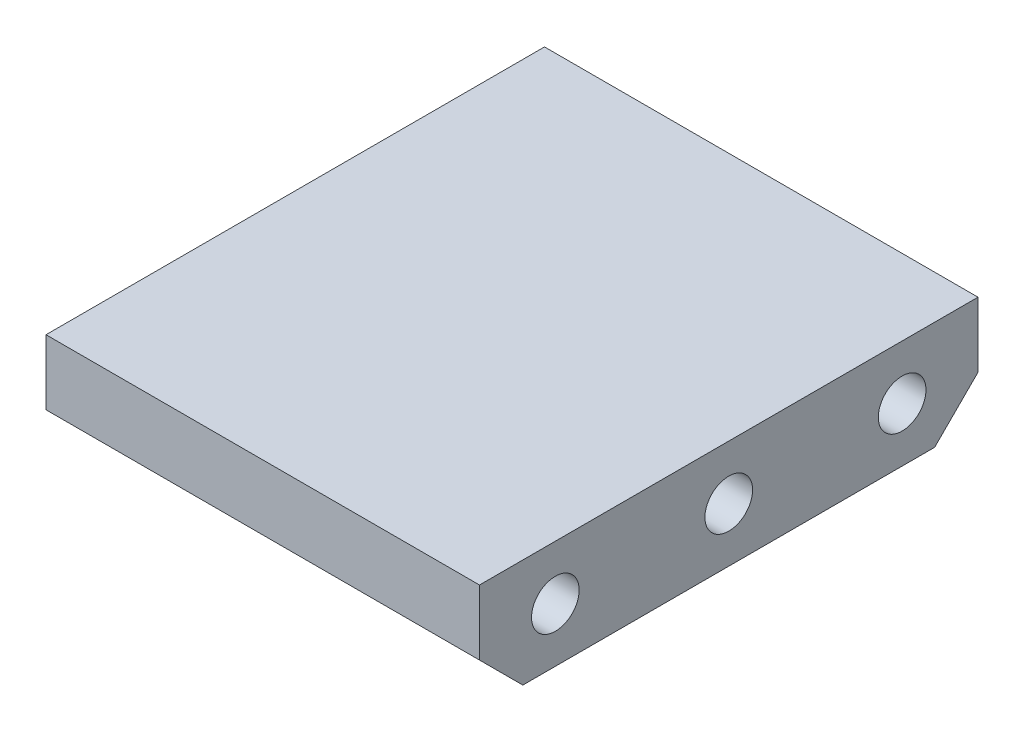
SolidWorks part; units mm, degrees
ref_plane "Ebene vorne" through (0, 0, 0) normal (0, 0, 1) x (1, 0, 0)
ref_plane "Ebene oben" through (0, 0, 0) normal (0, 1, 0) x (1, 0, 0)
ref_plane "Ebene rechts" through (0, 0, 0) normal (1, 0, 0) x (0, 0, -1)
sketch "Skizze1" plane through (0, 0, 0) normal (1, 0, 0) x (0, 0, -1)
  line L0 (-115, 0) -> (115, 0)
  line L1 (115, 0) -> (115, -30)
  line L2 (115, -30) -> (95, -50)
  line L3 (95, -50) -> (-95, -50)
  line L4 (0, 31.095) -> (0, -59.3631) construction
  line L5 (-115, -30) -> (-95, -50)
  line L6 (-115, 0) -> (-115, -30)
  circle A0 centre (0, -25) radius 11
  circle A1 centre (-80, -25) radius 11
  circle A2 centre (80, -25) radius 11
  point P9 (0, -50)
  point P11 (0, 0)
  dimension "D1" = 22
  dimension "D2" = 22
  dimension "D3" = 50
  dimension "D4" = 25
  dimension "D5" = 45
  dimension "D6" = 30
  dimension "D7" = 230
  dimension "D8" = 80
extrude "Aufsatz-Linear austragen1" add sketch "Skizze1" along normal mid plane 200
